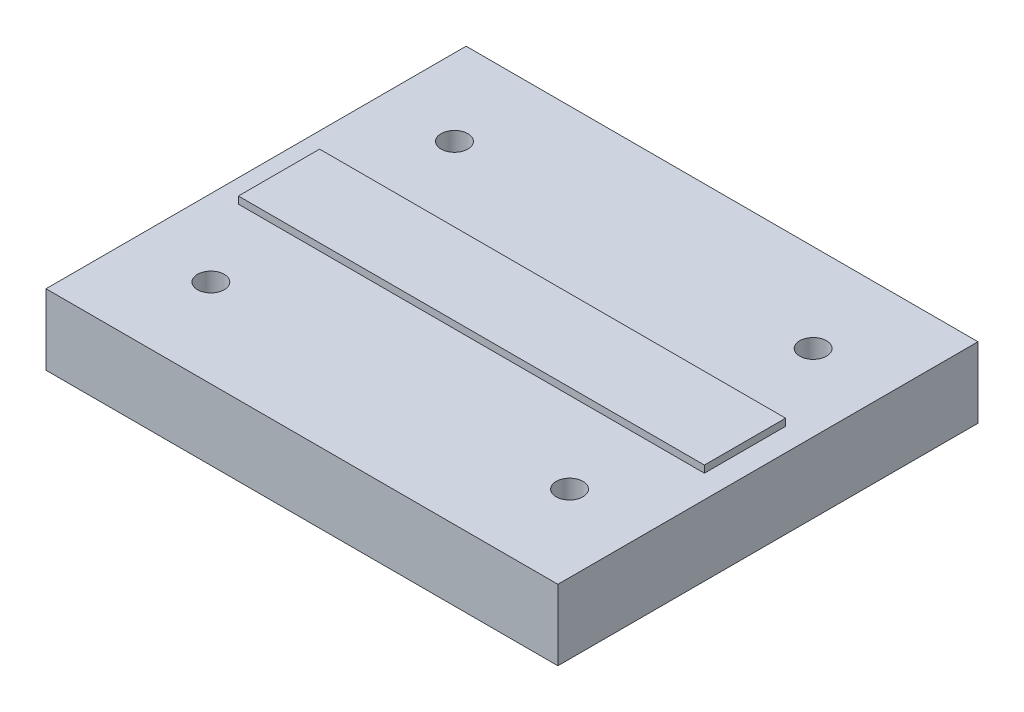
SolidWorks part; units mm, degrees
ref_plane "Front Plane" through (0, 0, 0) normal (0, 0, 1) x (1, 0, 0)
ref_plane "Top Plane" through (0, 0, 0) normal (0, 1, 0) x (1, 0, 0)
ref_plane "Right Plane" through (0, 0, 0) normal (1, 0, 0) x (0, 0, -1)
sketch "Sketch1" plane through (0, 0, 0) normal (0, 1, 0) x (1, 0, 0)
  line L1 (0, 0) -> (72.5, 0)
  line L2 (0, 0) -> (0, 59.5)
  line L3 (0, 59.5) -> (72.5, 59.5)
  line L4 (72.5, 0) -> (72.5, 59.5)
  dimension "D1" = 72.5
  dimension "D2" = 59.5
extrude "Boss-Extrude1" add sketch "Sketch1" along normal blind 10
sketch "Sketch4" plane through (0, 10, 0) normal (0, 1, 0) x (1, 0, 0)
  line L0 (0, 59.5) -> (0, 0) construction
  line L1 (3.25, 35.5) -> (69.25, 35.5)
  line L2 (3.25, 35.5) -> (3.25, 24)
  line L3 (3.25, 24) -> (69.25, 24)
  line L4 (69.25, 35.5) -> (69.25, 24)
  line L5 (72.5, 59.5) -> (0, 59.5) construction
  dimension "D1" = 3.25
  dimension "D2" = 66
  dimension "D3" = 11.5
  dimension "D4" = 24
extrude "Boss-Extrude3" add sketch "Sketch4" along normal blind 1
hole_wizard "Tap Drill for #10-24 Tap1" positions "Sketch6" profile "Sketch5" hole size "#10-24" standard "ANSI Inch" end condition through all
sketch "Sketch6" plane through (0, 10, 0) normal (0, 1, 0) x (1, 0, 0)
  line L0 (72.5, 59.5) -> (0, 59.5) construction
  line L1 (72.5, 0) -> (72.5, 59.5) construction
  line L2 (0, 0) -> (72.5, 0) construction
  point P0 (10.85, 47)
  point P2 (61.65, 47)
  point P4 (10.85, 12.5)
  point P6 (61.65, 12.5)
  dimension "D1" = 12.5
  dimension "D2" = 12.5
  dimension "D3" = 10.85
  dimension "D4" = 50.8
  dimension "D5" = 10.85
  dimension "D6" = 50.8
  dimension "D7" = 12.5
  dimension "D8" = 12.5
sketch "Sketch5" plane through (10.85, 10, -47) normal (1, 0, 0) x (0, 0, 1)
  line L0 (0, 0) -> (0, 10)
  line L1 (0, 10) -> (1.8986, 10)
  line L2 (1.8986, 10) -> (1.8986, 0)
  line L5 (1.8986, 0) -> (0, 0)
  line L11 (0, -6.35) -> (0, 107.95) construction
  dimension "Thru Hole Dia." = 3.7973
  dimension "Thru Hole Depth" = 10
